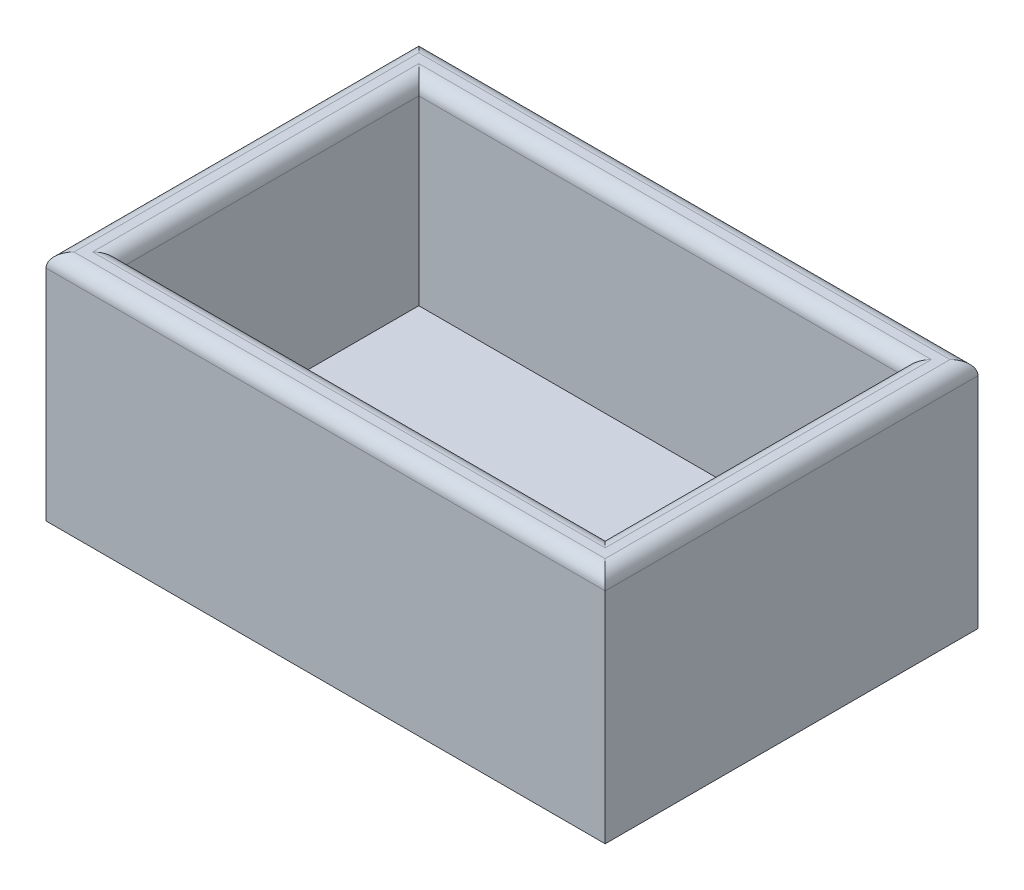
SolidWorks part; units mm, degrees
ref_plane "前视基准面" through (0, 0, 0) normal (0, 0, 1) x (1, 0, 0)
ref_plane "上视基准面" through (0, 0, 0) normal (0, 1, 0) x (1, 0, 0)
ref_plane "右视基准面" through (0, 0, 0) normal (1, 0, 0) x (0, 0, -1)
sketch "草图1" plane through (0, 0, 0) normal (0, 1, 0) x (1, 0, 0)
  line L0 (-60, 40) -> (60, 40)
  line L1 (60, 40) -> (60, -40)
  line L2 (60, -40) -> (-60, -40)
  line L3 (-60, -40) -> (-60, 40)
extrude "凸台-拉伸1" add sketch "草图1" along normal blind 50
ref_plane "基准面1" through (0, 50, 0) normal (0, 1, 0) x (1, 0, 0)
sketch "草图2" plane through (0, 50, 0) normal (0, 1, 0) x (1, 0, 0)
  line L0 (-52, 32) -> (52, 32)
  line L1 (52, 32) -> (52, -32)
  line L2 (52, -32) -> (-52, -32)
  line L3 (-52, -32) -> (-52, 32)
extrude "切除-拉伸1" cut sketch "草图2" against normal blind 42
fillet "圆角1" radius 3 8 edges at (0, 50, -32) (0, 50, 32) (-52, 50, 0) (52, 50, 0) (0, 50, -40) (0, 50, 40) (-60, 50, 0) (60, 50, 0)
